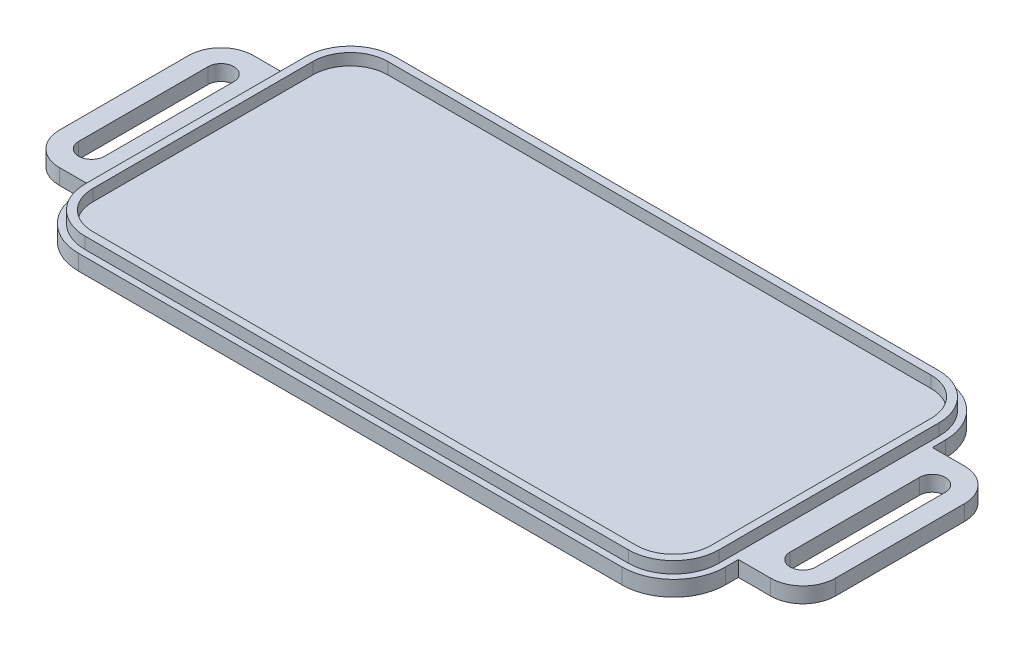
SolidWorks part; units mm, degrees
ref_plane "Front Plane" through (0, 0, 0) normal (0, 0, 1) x (1, 0, 0)
ref_plane "Top Plane" through (0, 0, 0) normal (0, 1, 0) x (1, 0, 0)
ref_plane "Right Plane" through (0, 0, 0) normal (1, 0, 0) x (0, 0, -1)
sketch "Sketch1" plane through (0, 0, 0) normal (0, 1, 0) x (1, 0, 0)
  line L0 (-59.6532, 31.2388) -> (-9.6532, 31.2388)
  line L1 (-59.6532, 31.2388) -> (-59.6532, 36.2388)
  line L2 (-59.6532, 56.2388) -> (-9.6532, 56.2388)
  line L3 (-9.6532, 31.2388) -> (-9.6532, 36.2388)
  line L4 (-9.6532, 51.2388) -> (-4.6532, 51.2388)
  line L5 (-64.6532, 51.2388) -> (-59.6532, 51.2388)
  line L6 (-64.6532, 51.2388) -> (-64.6532, 36.2388)
  line L7 (-64.6532, 36.2388) -> (-59.6532, 36.2388)
  line L8 (-4.6532, 51.2388) -> (-4.6532, 36.2388)
  line L9 (-9.6532, 36.2388) -> (-4.6532, 36.2388)
  line L10 (-59.6532, 51.2388) -> (-59.6532, 56.2388)
  line L11 (-9.6532, 51.2388) -> (-9.6532, 56.2388)
  dimension "D1" = 50
  dimension "D2" = 25
  dimension "D3" = 15
  dimension "D4" = 5
extrude "Boss-Extrude1" add sketch "Sketch1" along normal blind 1.2
fillet "Fillet1" radius 4 4 edges at (-59.6532, 0.6, -56.2388) (-9.6532, 0.6, -56.2388) (-9.6532, 0.6, -31.2388) (-59.6532, 0.6, -31.2388)
fillet "Fillet2" radius 2.5 4 edges at (-64.6532, 0.6, -36.2388) (-64.6532, 0.6, -51.2388) (-4.6532, 0.6, -51.2388) (-4.6532, 0.6, -36.2388)
sketch "Sketch4" plane through (0, 1.2, 0) normal (0, 1, 0) x (1, 0, 0)
  line L0 (-59.1532, 50.7388) -> (-59.1532, 36.7388)
  line L1 (-10.1532, 50.7388) -> (-10.1532, 36.7388)
  line L27 (-64.1532, 48.7388) -> (-64.1532, 38.7388)
  line L28 (-62.1532, 36.7388) -> (-59.1532, 36.7388)
  line L29 (-59.1532, 36.7388) -> (-59.1532, 35.2388)
  line L30 (-55.6532, 31.7388) -> (-13.6532, 31.7388)
  line L31 (-10.1532, 35.2388) -> (-10.1532, 36.7388)
  line L32 (-10.1532, 36.7388) -> (-7.1532, 36.7388)
  line L33 (-5.1532, 38.7388) -> (-5.1532, 48.7388)
  line L34 (-7.1532, 50.7388) -> (-10.1532, 50.7388)
  line L35 (-10.1532, 50.7388) -> (-10.1532, 52.2388)
  line L36 (-13.6532, 55.7388) -> (-55.6532, 55.7388)
  line L37 (-59.1532, 52.2388) -> (-59.1532, 50.7388)
  line L38 (-59.1532, 50.7388) -> (-62.1532, 50.7388)
  line L41 (-59.1532, 36.7388) -> (-59.1532, 35.2388)
  line L42 (-55.6532, 31.7388) -> (-13.6532, 31.7388)
  line L43 (-10.1532, 35.2388) -> (-10.1532, 36.7388)
  line L47 (-10.1532, 50.7388) -> (-10.1532, 52.2388)
  line L48 (-13.6532, 55.7388) -> (-55.6532, 55.7388)
  line L49 (-59.1532, 52.2388) -> (-59.1532, 50.7388)
  arc A16 (-64.1532, 38.7388) -> (-62.1532, 36.7388) centre (-62.1532, 38.7388) ccw
  arc A17 (-59.1532, 35.2388) -> (-55.6532, 31.7388) centre (-55.6532, 35.2388) ccw
  arc A18 (-13.6532, 31.7388) -> (-10.1532, 35.2388) centre (-13.6532, 35.2388) ccw
  arc A19 (-7.1532, 36.7388) -> (-5.1532, 38.7388) centre (-7.1532, 38.7388) ccw
  arc A20 (-5.1532, 48.7388) -> (-7.1532, 50.7388) centre (-7.1532, 48.7388) ccw
  arc A21 (-10.1532, 52.2388) -> (-13.6532, 55.7388) centre (-13.6532, 52.2388) ccw
  arc A22 (-55.6532, 55.7388) -> (-59.1532, 52.2388) centre (-55.6532, 52.2388) ccw
  arc A23 (-62.1532, 50.7388) -> (-64.1532, 48.7388) centre (-62.1532, 48.7388) ccw
  arc A25 (-59.1532, 35.2388) -> (-55.6532, 31.7388) centre (-55.6532, 35.2388) ccw
  arc A26 (-13.6532, 31.7388) -> (-10.1532, 35.2388) centre (-13.6532, 35.2388) ccw
  arc A29 (-10.1532, 52.2388) -> (-13.6532, 55.7388) centre (-13.6532, 52.2388) ccw
  arc A30 (-55.6532, 55.7388) -> (-59.1532, 52.2388) centre (-55.6532, 52.2388) ccw
  dimension "D1" = 0.5
extrude "Boss-Extrude2" add sketch "Sketch4" along normal blind 0.9
sketch "Sketch5" plane through (0, 2.1, 0) normal (0, 1, 0) x (1, 0, 0)
  line L8 (-58.5532, 52.2388) -> (-58.5532, 35.2388)
  line L9 (-55.6532, 32.3388) -> (-13.6532, 32.3388)
  line L10 (-10.7532, 35.2388) -> (-10.7532, 52.2388)
  line L11 (-13.6532, 55.1388) -> (-55.6532, 55.1388)
  line L12 (-58.5532, 52.2388) -> (-58.5532, 35.2388)
  line L13 (-55.6532, 32.3388) -> (-13.6532, 32.3388)
  line L14 (-10.7532, 35.2388) -> (-10.7532, 52.2388)
  line L15 (-13.6532, 55.1388) -> (-55.6532, 55.1388)
  arc A8 (-58.5532, 35.2388) -> (-55.6532, 32.3388) centre (-55.6532, 35.2388) ccw
  arc A9 (-13.6532, 32.3388) -> (-10.7532, 35.2388) centre (-13.6532, 35.2388) ccw
  arc A10 (-10.7532, 52.2388) -> (-13.6532, 55.1388) centre (-13.6532, 52.2388) ccw
  arc A11 (-55.6532, 55.1388) -> (-58.5532, 52.2388) centre (-55.6532, 52.2388) ccw
  arc A12 (-58.5532, 35.2388) -> (-55.6532, 32.3388) centre (-55.6532, 35.2388) ccw
  arc A13 (-13.6532, 32.3388) -> (-10.7532, 35.2388) centre (-13.6532, 35.2388) ccw
  arc A14 (-10.7532, 52.2388) -> (-13.6532, 55.1388) centre (-13.6532, 52.2388) ccw
  arc A15 (-55.6532, 55.1388) -> (-58.5532, 52.2388) centre (-55.6532, 52.2388) ccw
  dimension "D1" = 0.6
extrude "Cut-Extrude1" cut sketch "Sketch5" against normal blind 0.9
sketch "Sketch6" plane through (0, 1.2, 0) normal (0, 1, 0) x (1, 0, 0)
  line L2 (-63.1532, 48.7388) -> (-63.1532, 38.7388)
  line L3 (-61.1532, 48.7388) -> (-61.1532, 38.7388)
  line L4 (-8.1532, 48.7284) -> (-8.1532, 38.7388)
  line L5 (-6.1532, 48.7388) -> (-6.1532, 38.7388)
  arc A0 (-6.1532, 48.7388) -> (-8.1532, 48.7284) centre (-7.1532, 48.7388) ccw
  arc A1 (-8.1532, 38.7388) -> (-6.1532, 38.7388) centre (-7.1532, 38.7388) ccw
  arc A2 (-61.1532, 48.7388) -> (-63.1532, 48.7388) centre (-62.1532, 48.7388) ccw
  arc A3 (-63.1532, 38.7388) -> (-61.1532, 38.7388) centre (-62.1532, 38.7388) ccw
  arc A4 (-4.6532, 48.7388) -> (-7.1532, 51.2388) centre (-7.1532, 48.7388) ccw construction
  arc A6 (-7.1532, 36.2388) -> (-4.6532, 38.7388) centre (-7.1532, 38.7388) ccw construction
  arc A8 (-62.1532, 51.2388) -> (-64.6532, 48.7388) centre (-62.1532, 48.7388) ccw construction
  arc A10 (-64.6532, 38.7388) -> (-62.1532, 36.2388) centre (-62.1532, 38.7388) ccw construction
  dimension "D1" = 2
extrude "Cut-Extrude2" cut sketch "Sketch6" against normal through all contours L2 A3 L3 A2 | L4 A1 L5 A0
